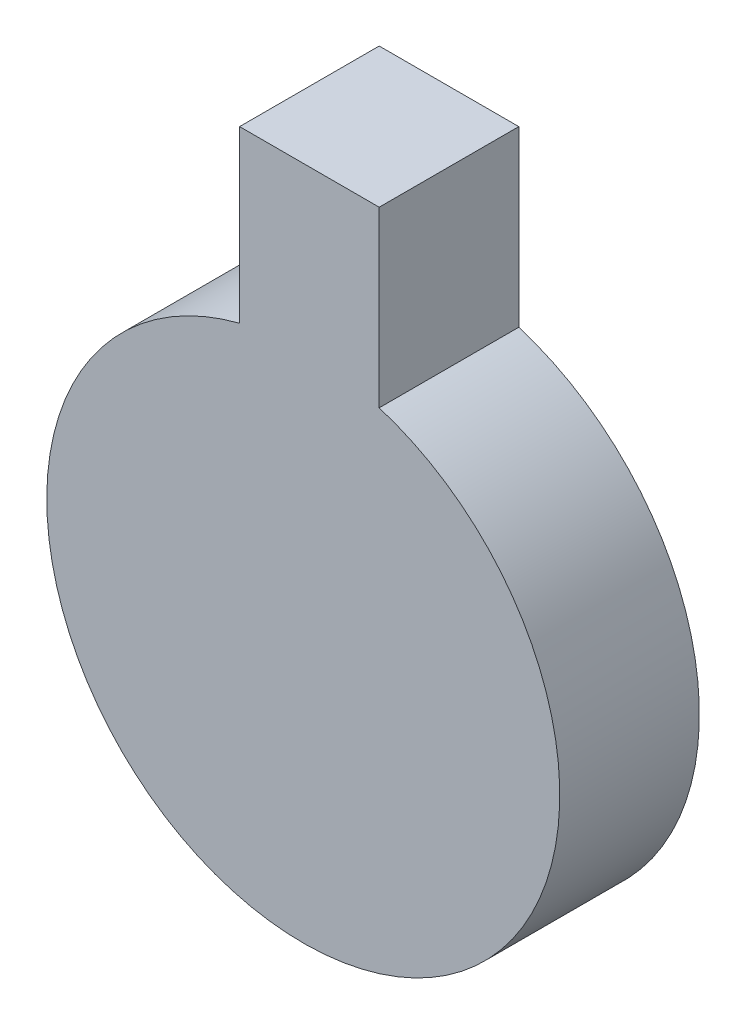
SolidWorks part; units mm, degrees
ref_plane "Front Plane" through (0, 0, 0) normal (0, 0, 1) x (1, 0, 0)
ref_plane "Top Plane" through (0, 0, 0) normal (0, 1, 0) x (1, 0, 0)
ref_plane "Right Plane" through (0, 0, 0) normal (1, 0, 0) x (0, 0, -1)
sketch "Sketch1" plane through (0, 0, 0) normal (0, 0, 1) x (1, 0, 0)
  circle A0 centre (0, 0) radius 0.0735
extrude "Boss-Extrude1" add sketch "Sketch1" along normal blind 0.04
sketch "Sketch2" plane through (0, 0, 0) normal (0, 1, 0) x (1, 0, 0)
  line L1 (0.0218, 0) -> (-0.0182, 0)
  line L2 (0.0218, 0) -> (0.0218, -0.04)
  line L3 (0.0218, -0.04) -> (-0.0182, -0.04)
  line L4 (-0.0182, 0) -> (-0.0182, -0.04)
  line L5 (0.0218, 0) -> (-0.0182, -0.04) construction
  line L6 (0.0218, -0.04) -> (-0.0182, 0) construction
  point P0 (0.0018, -0.02)
  dimension "D1" = 0.04
  dimension "D2" = 0.04
extrude "Boss-Extrude2" add sketch "Sketch2" along normal blind 0.12
